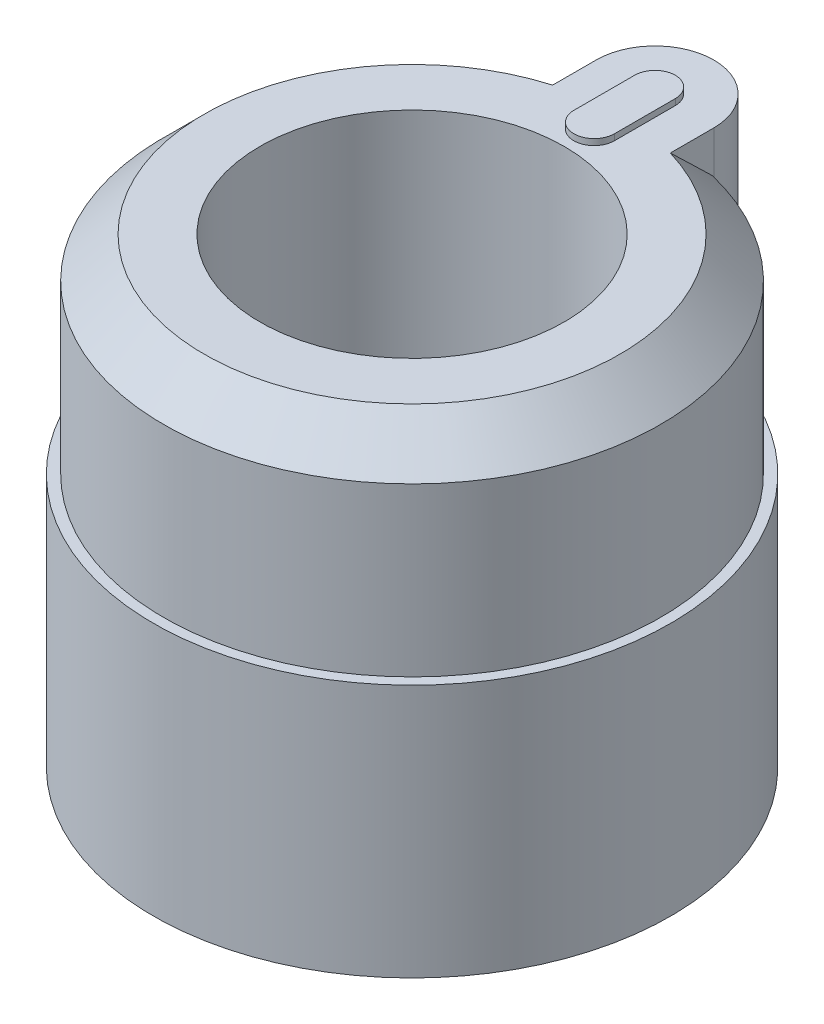
SolidWorks part; units mm, degrees
material "ABS PC"
ref_plane "Front Plane" through (0, 0, 0) normal (0, 0, 1) x (1, 0, 0)
ref_plane "Top Plane" through (0, 0, 0) normal (0, 1, 0) x (1, 0, 0)
ref_plane "Right Plane" through (0, 0, 0) normal (1, 0, 0) x (0, 0, -1)
sketch "Sketch1" plane through (0, 0, 0) normal (0, 0, 1) x (1, 0, 0)
  line L0 (12.75, 24.4) -> (0, 24.4)
  line L1 (0, 24.4) -> (0, 11.9)
  line L2 (0, 11.9) -> (12.75, 11.9)
  line L3 (12.75, 11.9) -> (12.75, 24.4)
  line L4 (0, 24.4) -> (0, 11.9) construction
revolve "Revolve1" add sketch "Sketch1" angle 360 about L4
sketch "Sketch2" plane through (0, 24.4, 0) normal (0, 1, 0) x (-1, 0, 0)
  line L0 (2.9, -11.9018) -> (2.9, -11.975)
  line L1 (-2.9, -11.975) -> (-2.9, -11.9018)
  arc A0 (-2.9, -11.9018) -> (2.9, -11.9018) centre (0, 0) cw
  arc A1 (2.9, -11.975) -> (-2.9, -11.975) centre (0, -11.975) cw
extrude "Boss-Extrude1" add sketch "Sketch2" along normal blind 10.24
sketch "Sketch3" plane through (0, 34.64, 0) normal (0, 1, 0) x (-1, 0, 0)
  line L0 (1, -8.975) -> (1, -11.975)
  line L1 (-1, -11.975) -> (-1, -8.975)
  arc A0 (1, -11.975) -> (-1, -11.975) centre (0, -11.975) cw
  arc A1 (-1, -8.975) -> (1, -8.975) centre (0, -8.975) cw
extrude "Boss-Extrude2" add sketch "Sketch3" along normal blind 0.3
hole_wizard "Ø15.0 (15) Diameter Hole1" positions "Sketch5" profile "Sketch4" hole size "Ø15.0" standard "ANSI Metric"
sketch "Sketch5" plane through (0, 11.9, 0) normal (0, -1, 0) x (-1, 0, 0)
  point P0 (0, 0)
sketch "Sketch4" plane through (0, 11.9, 0) normal (1, 0, 0) x (0, 0, -1)
  line L0 (0, 0) -> (0, 23.04)
  line L1 (0, 23.04) -> (7.5, 23.04)
  line L2 (7.5, 23.04) -> (7.5, 0)
  line L5 (7.5, 0) -> (0, 0)
  line L11 (0, -6.35) -> (0, 107.95) construction
  dimension "Thru Hole Dia." = 15
  dimension "Thru Hole Depth" = 23.04
chamfer "Chamfer1" distance 2 angle 45 1 edges at (0, 34.64, 12.25)
